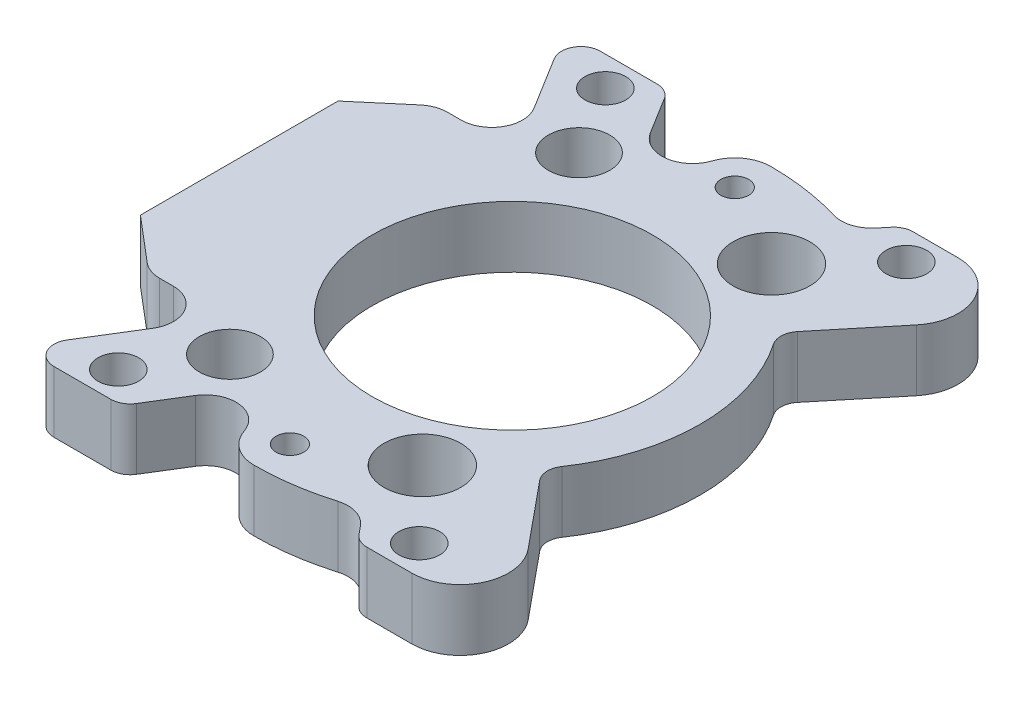
SolidWorks part; units mm, degrees
ref_plane "Front Plane" through (0, 0, 0) normal (0, 0, 1) x (1, 0, 0)
ref_plane "Top Plane" through (0, 0, 0) normal (0, 1, 0) x (1, 0, 0)
ref_plane "Right Plane" through (0, 0, 0) normal (1, 0, 0) x (0, 0, -1)
sketch "Sketch1" plane through (0, 0, 0) normal (0, 1, 0) x (1, 0, 0)
  line L0 (0, 56.515) -> (56.515, 0) construction
  line L1 (0, 0) -> (56.515, 0)
  line L2 (0, 0) -> (0, 56.515)
  line L3 (0, 56.515) -> (56.515, 56.515)
  line L4 (56.515, 0) -> (56.515, 56.515)
  line L6 (12.6873, 3.0607) -> (43.8277, 3.0607) construction
  line L7 (12.6873, 3.0607) -> (12.6873, 53.4543) construction
  line L8 (12.6873, 53.4543) -> (43.8277, 53.4543) construction
  line L9 (43.8277, 3.0607) -> (43.8277, 53.4543) construction
  line L10 (12.6873, 3.0607) -> (43.8277, 53.4543) construction
  line L11 (12.6873, 53.4543) -> (43.8277, 3.0607) construction
  circle A0 centre (43.8277, 3.0607) radius 2.1082
  circle A1 centre (12.6873, 3.0607) radius 2.1082
  circle A2 centre (12.6873, 53.4543) radius 2.1082
  circle A3 centre (43.8277, 53.4543) radius 2.1082
  circle A4 centre (28.2575, 28.2575) radius 14.5
  point P5 (28.2575, 28.2575)
  point P6 (28.2575, 28.2575)
  dimension "D5" = 4.2164
  dimension "D6" = 29
  dimension "D1" = 56.515
  dimension "D2" = 56.515
  dimension "D3" = 31.1404
  dimension "D4" = 50.3936
extrude "Boss-Extrude1" add sketch "Sketch1" along normal blind 6.35
sketch "Sketch3" plane through (0, 6.35, 0) normal (0, 1, 0) x (1, 0, 0)
  line L0 (51.5305, 0) -> (38.0741, 16.3385) construction
  line L1 (37.1401, 4.8887) -> (41.1665, 0) construction
  line L2 (0, 0) -> (56.515, 0) construction
  line L3 (43.8277, 3.0607) -> (-7.9833, 65.9682) construction
  line L4 (51.5305, 0) -> (41.1665, 0) construction
  line L5 (0, 18.6883) -> (7.198, 12.5871) construction
  line L6 (0.2175, 18.5039) -> (5.6815, 13.8725) construction
  line L7 (0, 56.515) -> (0, 0) construction
  line L8 (5.6815, 13.8725) -> (22.645, 13.8725) construction
  line L9 (22.645, 13.8725) -> (25.7282, 2.1296) construction
  line L10 (25.1261, 4.4228) -> (22.645, 13.8725) construction
  line L11 (23.0701, 12.2536) -> (15.4981, 0) construction
  line L12 (14.6663, 13.8725) -> (6.0939, 0) construction
  line L13 (12.6873, 3.0607) -> (50.1607, 63.7028) construction
  line L14 (5.6815, 13.8725) -> (22.645, 13.8725) construction
  line L15 (41.1665, 0) -> (37.9766, 3.8731)
  line L16 (23.0701, 12.2536) -> (25.1261, 4.4228)
  line L17 (23.0701, 12.2536) -> (15.4981, 0)
  line L18 (40.9306, -0.5) -> (37.821, 3.2755) construction
  line L19 (22.8825, 10.9989) -> (24.6425, 4.2958) construction
  line L20 (40.5187, 0) -> (39.2133, 1.585)
  line L21 (51.5305, 0) -> (38.0741, 16.3385) construction
  line L22 (19.0019, 4.7189) -> (16.0858, 0)
  line L23 (40.5187, 0) -> (16.0858, 0)
  line L24 (6.0939, 0) -> (14.6663, 13.8725)
  line L25 (14.6663, 13.8725) -> (5.6815, 13.8725)
  line L26 (5.6815, 13.8725) -> (0, 18.6883)
  line L27 (5.6685, 0.2628) -> (10.7762, 8.5285)
  line L28 (8.0753, 13.3725) -> (6.6627, 13.3725)
  line L29 (4.6098, 14.1255) -> (0, 18.0328)
  line L30 (5.6685, 0.2628) -> (13.7696, 13.3725) construction
  line L31 (13.7696, 13.3725) -> (5.4982, 13.3725) construction
  line L32 (5.4982, 13.3725) -> (-0.3233, 18.3068) construction
  line L33 (0, 0) -> (0, 18.0328)
  line L34 (0, 0) -> (5.5061, 0)
  line L35 (5.6685, 0.2628) -> (5.5061, 0)
  line L36 (22.8825, 10.9989) -> (15.9234, -0.2628) construction
  line L37 (52.5901, -0.5) -> (38.46, 16.6563) construction
  line L38 (52.5901, -0.5) -> (40.9306, -0.5) construction
  line L39 (56.515, 28.2575) -> (28.2575, 28.2575) construction
  line L40 (56.515, 0) -> (56.515, 56.515) construction
  line L41 (51.5305, 56.515) -> (38.0741, 40.1765) construction
  line L42 (54.6181, 53.972) -> (44.4315, 41.6037)
  line L43 (54.6181, 2.543) -> (44.4315, 14.9113)
  line L44 (54.6181, 53.972) -> (43.4402, 40.4001) construction
  line L45 (54.6181, 2.543) -> (43.4402, 16.1149) construction
  line L48 (56.515, 56.515) -> (0, 56.515) construction
  line L50 (56.515, 56.515) -> (56.515, 0)
  line L52 (0, 56.515) -> (5.5061, 56.515)
  line L53 (5.6685, 56.2522) -> (5.5061, 56.515)
  line L54 (5.6685, 56.2522) -> (10.7762, 47.9865)
  line L55 (8.0753, 43.1425) -> (6.6627, 43.1425)
  line L56 (4.6098, 42.3895) -> (0, 38.4822)
  line L57 (0, 56.515) -> (0, 38.4822)
  line L58 (40.5187, 56.515) -> (16.0858, 56.515)
  line L59 (40.5187, 56.515) -> (39.2133, 54.93)
  line L60 (19.0019, 51.7961) -> (16.0858, 56.515)
  line L61 (37.0084, 10.1975) -> (8.0753, 10.1975) construction
  line L62 (33.87, 13.8725) -> (31.3889, 4.4228) construction
  circle A0 centre (28.2575, 51.27) radius 1.435
  circle A1 centre (28.2575, 5.245) radius 1.435
  arc A2 (33.87, 13.8725) -> (33.87, 42.6425) centre (28.2575, 28.2575) ccw construction
  circle A3 centre (28.2575, 28.2575) radius 14.5 construction
  circle A4 centre (28.2575, 28.2575) radius 25 construction
  circle A5 centre (28.2575, 28.2575) radius 26.25 construction
  arc A6 (25.1261, 4.4228) -> (31.3889, 4.4228) centre (28.2575, 5.245) ccw construction
  arc A7 (7.198, 12.5871) -> (37.9766, 3.8731) centre (28.2575, 28.2575) ccw construction
  circle A8 centre (28.2575, 28.2575) radius 14.5 construction
  circle A9 centre (28.2575, 5.245) radius 1.435 construction
  circle A10 centre (28.2575, 51.27) radius 1.435 construction
  arc A11 (37.9766, 3.8731) -> (28.2575, 2.0075) centre (28.2575, 28.2575) cw
  arc A12 (25.1261, 4.4228) -> (28.2575, 2.0075) centre (28.2575, 5.245) ccw
  arc A13 (35.8601, 2.6106) -> (28.2575, 1.5075) centre (28.2575, 28.2575) cw
  arc A14 (24.7134, 4.0582) -> (28.2575, 1.5075) centre (28.2575, 5.245) ccw
  arc A15 (37.821, 3.2755) -> (28.2575, 1.5075) centre (28.2575, 28.2575) cw construction
  arc A16 (10.7762, 8.5285) -> (8.0753, 13.3725) centre (8.0753, 10.1975) ccw
  arc A17 (4.6098, 14.1255) -> (6.6627, 13.3725) centre (6.6627, 16.5475) ccw
  arc A18 (39.2133, 1.585) -> (35.8601, 2.6106) centre (36.7625, -0.4334) ccw
  arc A19 (24.7134, 4.0582) -> (19.0019, 4.7189) centre (21.7028, 3.0499) ccw
  arc A20 (38.0741, 40.1765) -> (38.0741, 16.3385) centre (28.2575, 28.2575) cw
  arc A21 (24.6425, 4.2958) -> (28.2575, 1.5075) centre (28.2575, 5.245) ccw construction
  arc A22 (44.3226, 39.2059) -> (44.3226, 17.3091) centre (28.2575, 28.2575) cw
  arc A23 (43.4402, 40.4001) -> (43.4402, 16.1149) centre (28.2575, 28.2575) cw construction
  arc A24 (44.3226, 39.2059) -> (44.4315, 41.6037) centre (45.9753, 40.3323) cw
  arc A25 (44.4315, 14.9113) -> (44.3226, 17.3091) centre (45.9753, 16.1827) cw
  arc A26 (10.7762, 47.9865) -> (8.0753, 43.1425) centre (8.0753, 46.3175) cw
  arc A27 (4.6098, 42.3895) -> (6.6627, 43.1425) centre (6.6627, 39.9675) cw
  arc A28 (39.2133, 54.93) -> (35.8601, 53.9044) centre (36.7625, 56.9484) cw
  arc A29 (35.8601, 53.9044) -> (28.2575, 55.0075) centre (28.2575, 28.2575) ccw
  arc A30 (24.7134, 52.4568) -> (28.2575, 55.0075) centre (28.2575, 51.27) cw
  arc A31 (24.7134, 52.4568) -> (19.0019, 51.7961) centre (21.7028, 53.4651) cw
  circle A32 centre (37.0084, 10.1975) radius 3.9687
  circle A33 centre (17.0974, 10.1975) radius 3.175
  circle A34 centre (17.0974, 46.3175) radius 3.175
  circle A35 centre (37.0084, 46.3175) radius 3.9688
  arc A36 (46.117, 0) -> (49.9765, 8.1787) centre (46.117, 5) ccw
  arc A38 (46.117, 56.515) -> (49.9765, 48.3363) centre (46.117, 51.515) cw
  point P60 (18.0224, 4.0851)
  point P84 (36.3745, 41.393)
  point P113 (0, 0)
  point P114 (50.6977, 49.2119)
  point P115 (56.0653, 55.7291)
  point P121 (57.9114, -1.4557)
  dimension "D1" = 50
  dimension "D4" = 29
  dimension "D11" = 3.175
  dimension "D12" = 3.175
  dimension "D8" = 3.175
  dimension "D9" = 3.175
  dimension "D14" = 2
  dimension "D15" = 2
  dimension "D16" = 7.9375
  dimension "D17" = 6.35
  dimension "D19" = 5
  dimension "D2" = 8
  dimension "D3" = 4
  dimension "D5" = 8
  dimension "D6" = 4
  dimension "D10" = 0.5
  dimension "D7" = 0.5
  dimension "D13" = 4
extrude "Cut-Extrude1" cut sketch "Sketch3" against normal through all
fillet "Fillet1" radius 2 6 edges at (5.5061, 3.175, 0) (5.5061, 3.175, -56.515) (40.5187, 3.175, 0) (16.0858, 3.175, 0) (16.0858, 3.175, -56.515) (40.5187, 3.175, -56.515)
sketch "Sketch4" plane through (0, 6.35, 0) normal (0, 1, 0) x (1, 0, 0)
  circle A0 centre (12.6873, 53.4543) radius 2.1082 construction
  circle A1 centre (12.6873, 3.0607) radius 2.1082 construction
  circle A2 centre (43.8277, 3.0607) radius 2.1082 construction
  circle A3 centre (43.8277, 53.4543) radius 2.1082 construction
  circle A4 centre (12.6873, 53.4543) radius 2.1082 construction
  circle A5 centre (12.6873, 3.0607) radius 2.1082 construction
  circle A6 centre (43.8277, 3.0607) radius 2.1082 construction
  circle A7 centre (43.8277, 53.4543) radius 2.1082 construction
  circle A8 centre (43.8277, 53.4543) radius 3.3655 construction
  circle A9 centre (12.6873, 53.4543) radius 3.3655 construction
  circle A10 centre (43.8277, 3.0607) radius 3.3655 construction
  circle A11 centre (12.6873, 3.0607) radius 3.3655 construction
  dimension "D1" = 6.731
equation "\"D3@Sketch3\"=\"D2@Sketch3\"/2"
